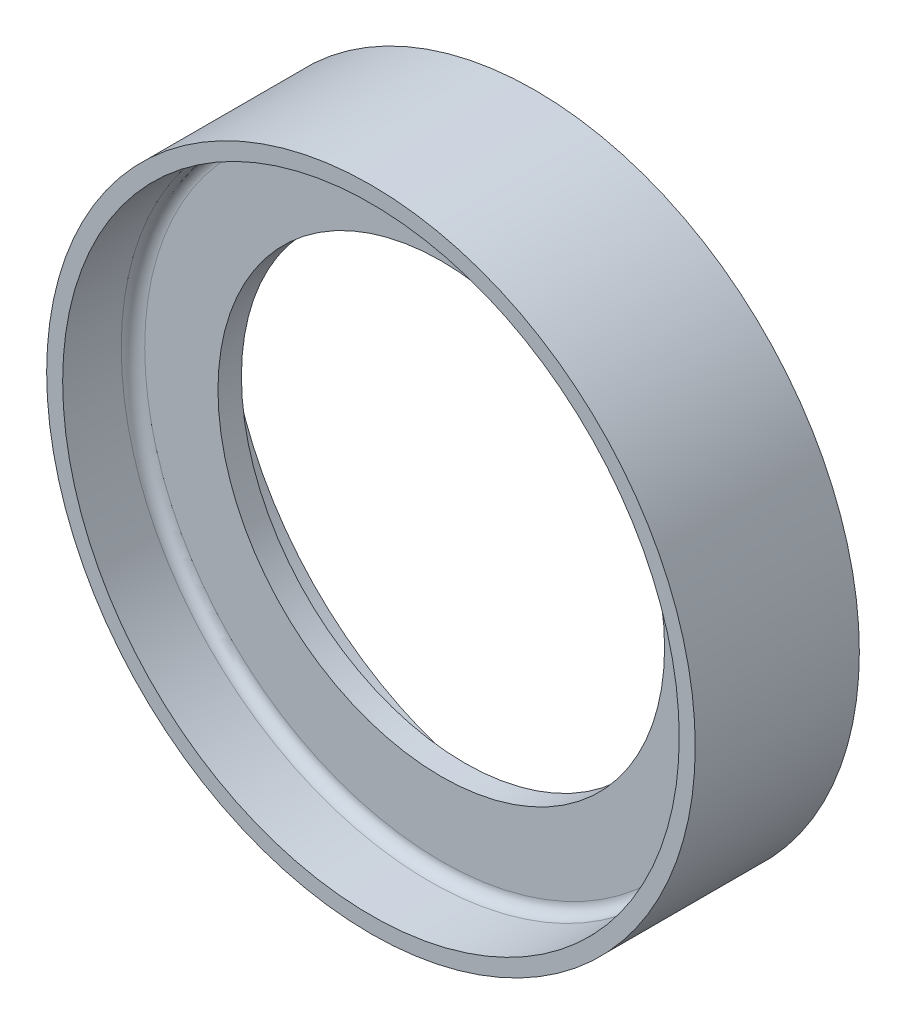
SolidWorks part; units mm, degrees
ref_plane "Front Plane" through (0, 0, 0) normal (0, 0, 1) x (1, 0, 0)
ref_plane "Top Plane" through (0, 0, 0) normal (0, 1, 0) x (1, 0, 0)
ref_plane "Right Plane" through (0, 0, 0) normal (1, 0, 0) x (0, 0, -1)
sketch "Sketch1" plane through (0, 0, 0) normal (0, 0, 1) x (1, 0, 0)
  circle A4 centre (0, 0) radius 13.8327
  circle A5 centre (0, 0) radius 13.15
  circle A6 centre (0, 0) radius 13.15
  dimension "D1" = 0.15
  dimension "D3" = 0.6827
  dimension "D2" = 27.6654
extrude "Boss-Extrude1" add sketch "Sketch1" against normal blind 3
sketch "Sketch2" plane through (0, 0, 0) normal (0, 0, 1) x (1, 0, 0)
  circle A0 centre (0, 0) radius 13.8327
  circle A1 centre (0, 0) radius 9.525
  dimension "D1" = 19.05
extrude "Boss-Extrude2" add sketch "Sketch2" along normal blind 1
sketch "Sketch3" plane through (0, 0, 1) normal (0, 0, 1) x (1, 0, 0)
  circle A0 centre (0, 0) radius 13.15 construction
  circle A1 centre (0, 0) radius 13.8327
  circle A2 centre (0, 0) radius 13.8327
  circle A3 centre (0, 0) radius 13.15
  dimension "D1" = 0
extrude "Boss-Extrude3" add sketch "Sketch3" along normal blind 3
fillet "Fillet1" radius 0.5 2 edges at (13.15, 0, 1) (13.15, 0, 0)
